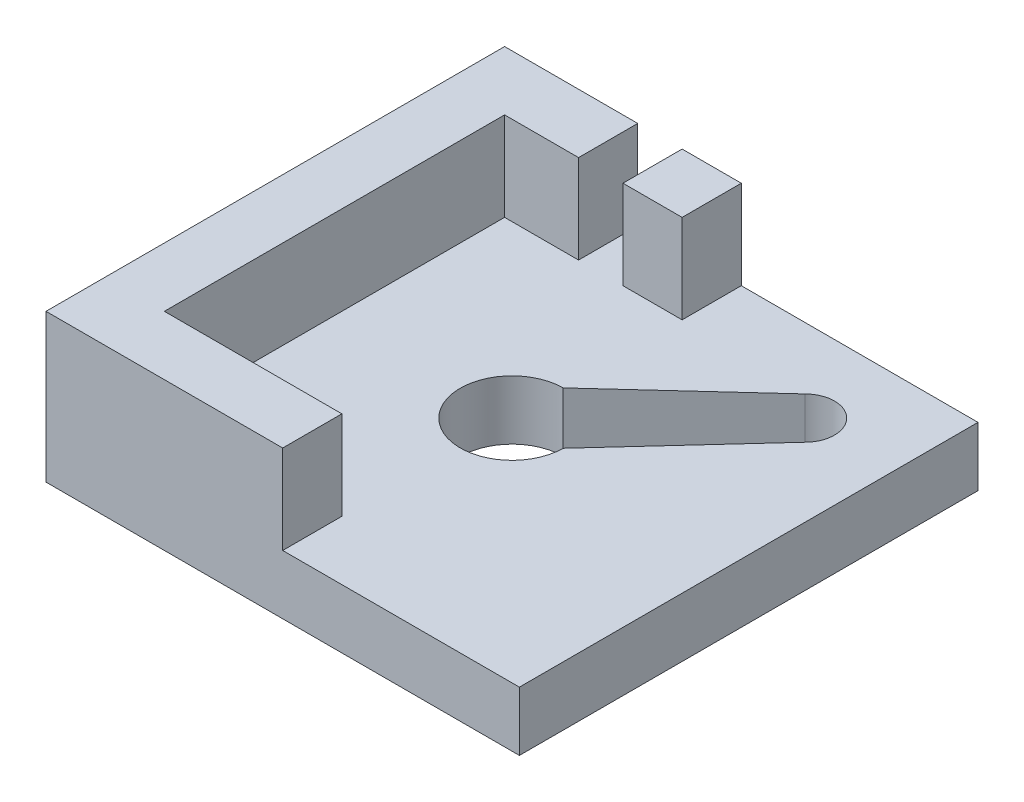
SolidWorks part; units mm, degrees
ref_plane "Front Plane" through (0, 0, 0) normal (0, 0, 1) x (1, 0, 0)
ref_plane "Top Plane" through (0, 0, 0) normal (0, 1, 0) x (1, 0, 0)
ref_plane "Right Plane" through (0, 0, 0) normal (1, 0, 0) x (0, 0, -1)
sketch "Sketch1" plane through (0, 0, 0) normal (0, 1, 0) x (1, 0, 0)
  line L1 (-16, -15.5) -> (16, -15.5)
  line L2 (-16, -15.5) -> (-16, 15.5)
  line L3 (-16, 15.5) -> (16, 15.5)
  line L4 (16, -15.5) -> (16, 15.5)
  line L5 (-16, -15.5) -> (16, 15.5) construction
  line L6 (-16, 15.5) -> (16, -15.5) construction
  point P0 (0, 0)
  dimension "D1" = 32
  dimension "D2" = 31
extrude "Boss-Extrude1" add sketch "Sketch1" along normal blind 4
sketch "Sketch2" plane through (0, 4, 0) normal (0, 1, 0) x (1, 0, 0)
  line L0 (-16, 15.5) -> (-16, -15.5)
  line L1 (-16, -15.5) -> (0, -15.5)
  line L2 (-16, -15.5) -> (16, -15.5) construction
  line L3 (0, -15.5) -> (0, -11.5)
  line L4 (-16, 15.5) -> (0, 15.5)
  line L5 (16, 15.5) -> (-16, 15.5) construction
  line L6 (0, 15.5) -> (0, 11.5)
  line L7 (0, 11.5) -> (-12, 11.5)
  line L8 (-12, 11.5) -> (-12, -11.5)
  line L9 (-12, -11.5) -> (0, -11.5)
  dimension "D1" = 4
  dimension "D2" = 16
  dimension "D3" = 31
  dimension "D4" = 16
  dimension "D5" = 4
  dimension "D6" = 4
extrude "Boss-Extrude2" add sketch "Sketch2" along normal blind 6
sketch "Sketch3" plane through (0, 10, 0) normal (0, 1, 0) x (1, 0, 0)
  line L0 (0, 15.5) -> (-16, 15.5) construction
  line L1 (-7, 15.5) -> (-4, 15.5)
  line L2 (-7, 15.5) -> (-7, 11.5)
  line L3 (-7, 11.5) -> (-4, 11.5)
  line L4 (-4, 15.5) -> (-4, 11.5)
  line L5 (-12, 11.5) -> (0, 11.5) construction
  dimension "D1" = 5
  dimension "D2" = 3
extrude "Cut-Extrude1" cut sketch "Sketch3" against normal blind 6
sketch "Sketch4" plane through (0, 4, 0) normal (0, 1, 0) x (0.7071, 0, -0.7071)
  line L0 (0, 0) -> (0, 2.5) construction
  line L1 (0, 0) -> (0, -2.5) construction
  line L2 (0, 0) -> (16, 0) construction
  line L4 (0, -2.5) -> (2.4495, -2.5) construction
  line L5 (2.4495, 2.5) -> (14, 2)
  line L7 (0, 2.5) -> (2.4495, 2.5) construction
  line L10 (16, 0) -> (14, 2) construction
  line L11 (16, 0) -> (14, -2) construction
  line L12 (2.4495, -2.5) -> (14, -2)
  circle A0 centre (0, 0) radius 3.5
  arc A3 (2.4495, 2.5) -> (2.4495, -2.5) centre (0, 0) cw
  arc A4 (16, 0) -> (14, 2) centre (14, 0) ccw
  arc A5 (16, 0) -> (14, -2) centre (14, 0) cw
  dimension "D1" = 7
  dimension "D2" = 16
  dimension "D3" = 45
  dimension "D4" = 45
  dimension "D5" = 2
  dimension "D6" = 2.5
  dimension "D7" = 2.5
  dimension "D8" = 2
extrude "Cut-Extrude6" cut sketch "Sketch4" against normal blind 4
